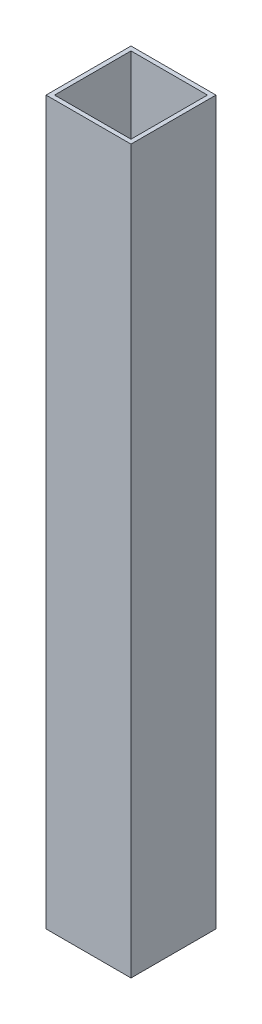
SolidWorks part; units mm, degrees
ref_plane "Ön Düzlem" through (0, 0, 0) normal (0, 0, 1) x (1, 0, 0)
ref_plane "Üst Düzlem" through (0, 0, 0) normal (0, 1, 0) x (1, 0, 0)
ref_plane "Sağ Düzlem" through (0, 0, 0) normal (1, 0, 0) x (0, 0, -1)
sketch "Sketch1" plane through (0, 0, 0) normal (0, 1, 0) x (1, 0, 0)
  line L1 (0, 0) -> (-40, 0)
  line L2 (0, 0) -> (0, 40)
  line L3 (0, 40) -> (-40, 40)
  line L4 (-40, 0) -> (-40, 40)
  dimension "D1" = 40
extrude "Extrude-Thin1" add sketch "Sketch1" along normal blind 340 thin
